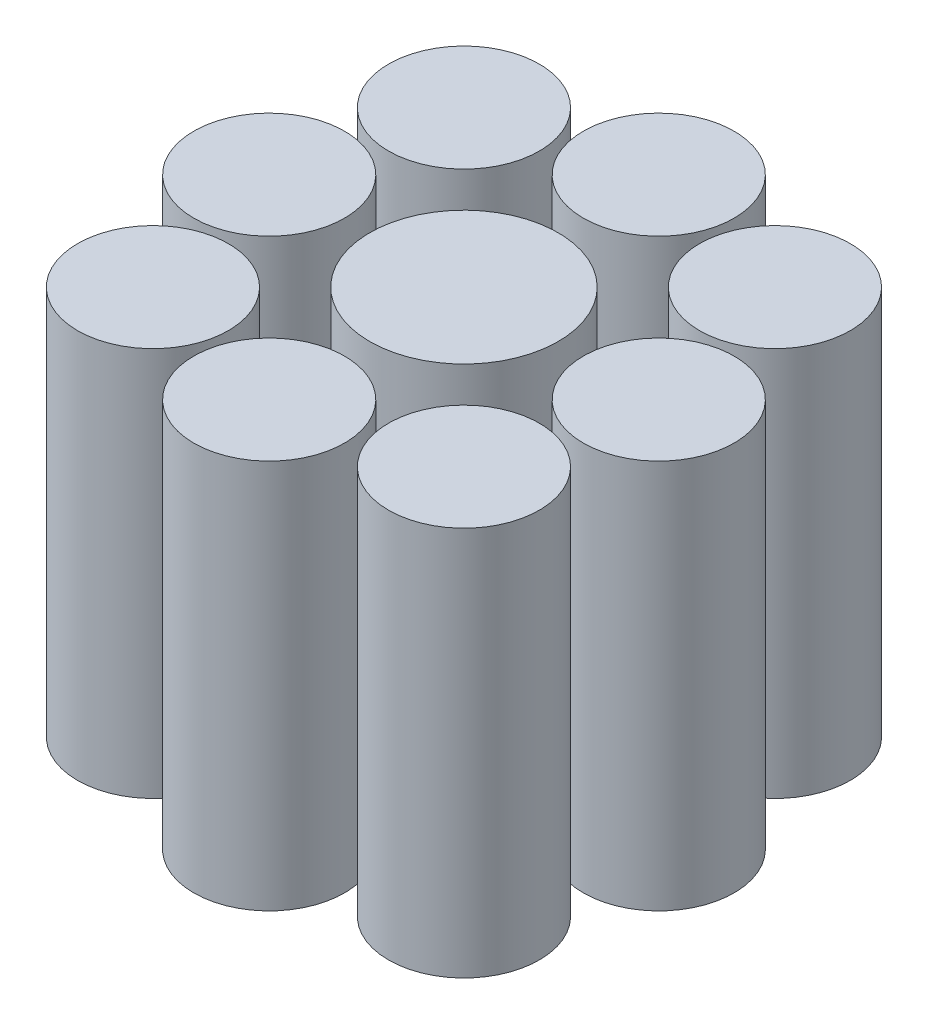
SolidWorks part; units mm, degrees
ref_plane "前视基准面" through (0, 0, 0) normal (0, 0, 1) x (1, 0, 0)
ref_plane "上视基准面" through (0, 0, 0) normal (0, 1, 0) x (1, 0, 0)
ref_plane "右视基准面" through (0, 0, 0) normal (1, 0, 0) x (0, 0, -1)
sketch "草图1" plane through (0, 0, 0) normal (0, 1, 0) x (1, 0, 0)
  line L0 (0, 0) -> (27, 0) construction
  line L1 (0, 0) -> (27, -27) construction
  line L2 (27, 0) -> (27, -27) construction
  circle A0 centre (0, 0) radius 12
  circle A1 centre (27, 0) radius 12
  circle A2 centre (0, -27) radius 12
  circle A3 centre (-27, 0) radius 12
  circle A4 centre (0, 27) radius 12
  circle A5 centre (27, -27) radius 12
  circle A6 centre (-27, -27) radius 12
  circle A7 centre (-27, 27) radius 12
  circle A8 centre (27, 27) radius 12
  point P6 (36.945, 27)
  point P14 (0, 0)
  point P15 (0, 0)
  point P23 (0, 0)
  dimension "D1" = 24
  dimension "D2" = 27
  dimension "D4" = 45
  dimension "D3" = 4
  dimension "D5" = 4
extrude "凸台-拉伸1" [suppressed] add sketch "草图1" along normal blind 62
sketch "草图2" plane through (0, 0, 0) normal (0, 1, 0) x (1, 0, 0)
  line L0 (0, 0) -> (31, 0) construction
  line L1 (0, 0) -> (24.7487, -24.7487) construction
  circle A0 centre (0, 0) radius 15
  circle A1 centre (31, 0) radius 12
  circle A2 centre (0, -31) radius 12
  circle A3 centre (-31, 0) radius 12
  circle A4 centre (0, 31) radius 12
  circle A5 centre (24.7487, -24.7487) radius 12
  circle A6 centre (-24.7487, -24.7487) radius 12
  circle A7 centre (-24.7487, 24.7487) radius 12
  circle A8 centre (24.7487, 24.7487) radius 12
  point P6 (30.334, 25.9969)
  point P7 (0, 0)
  point P14 (0, 0)
  point P23 (0, 0)
  dimension "D1" = 30
  dimension "D2" = 24
  dimension "D6" = 24
  dimension "D3" = 31
  dimension "D5" = 45
  dimension "D7" = 35
  dimension "D4" = 4
  dimension "D8" = 4
extrude "凸台-拉伸2" add sketch "草图2" along normal blind 62
